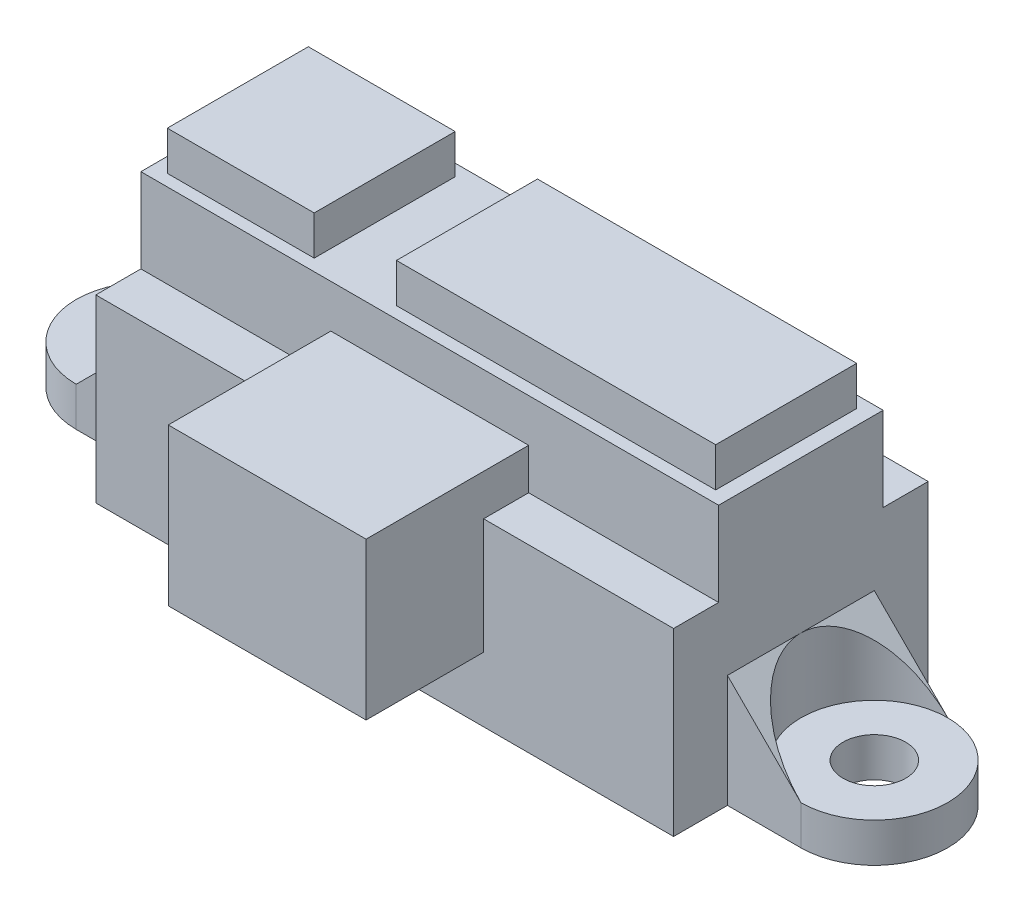
SolidWorks part; units mm, degrees
ref_plane "Plan de face" through (0, 0, 0) normal (0, 0, 1) x (1, 0, 0)
ref_plane "Plan de dessus" through (0, 0, 0) normal (0, 1, 0) x (1, 0, 0)
ref_plane "Plan de droite" through (0, 0, 0) normal (1, 0, 0) x (0, 0, -1)
sketch "Sketch1" plane through (0, 0, 0) normal (0, 1, 0) x (1, 0, 0)
  line L1 (-18.5, -3.75) -> (18.5, -3.75)
  line L2 (-18.5, -3.75) -> (-18.5, 3.75) construction
  line L3 (-18.5, 3.75) -> (18.5, 3.75)
  line L4 (18.5, -3.75) -> (18.5, 3.75) construction
  line L5 (-18.5, -3.75) -> (18.5, 3.75) construction
  line L6 (-18.5, 3.75) -> (18.5, -3.75) construction
  arc A0 (18.5, -3.75) -> (18.5, 3.75) centre (18.5, 0) ccw
  arc A1 (-18.5, 3.75) -> (-18.5, -3.75) centre (-18.5, 0) ccw
  circle A2 centre (18.5, 0) radius 1.6
  circle A3 centre (-18.5, 0) radius 1.6
  point P0 (0, 0)
  dimension "D1" = 3.75
  dimension "D2" = 3.2
  dimension "D3" = 37
extrude "Extrude1" add sketch "Sketch1" along normal blind 10
sketch "Sketch2" plane through (0, 0, 3.75) normal (0, 0, 1) x (1, 0, 0)
  line L0 (-22.25, 0) -> (-18.5, 0) construction
  line L1 (-22.25, 10) -> (-22.25, 0) construction
  line L2 (-22.25, 2) -> (-18.5, 2)
  line L3 (-18.5, 10) -> (-18.5, 0) construction
  line L4 (-18.5, 2) -> (-10.5, 10)
  line L5 (-18.5, 10) -> (18.5, 10) construction
  line L6 (-10.5, 10) -> (10.5, 10)
  line L7 (10.5, 10) -> (18.5, 2)
  line L8 (18.5, 10) -> (18.5, 0) construction
  line L9 (18.5, 2) -> (22.25, 2)
  line L10 (22.25, 2) -> (22.25, 12)
  line L11 (22.25, 12) -> (-22.25, 12)
  line L12 (-22.25, 12) -> (-22.25, 2)
  line L13 (-18.5, 10) -> (-22.25, 10) construction
  line L14 (22.25, 0) -> (22.25, 10) construction
  dimension "D1" = 2
  dimension "D2" = 2
  dimension "D3" = 45
  dimension "D4" = 45
extrude "Extrude2" cut sketch "Sketch2" against normal blind 10
sketch "Sketch3" plane through (0, 2, 0) normal (0, 1, 0) x (1, 0, 0)
  circle A0 centre (-18.5, 0) radius 3.75
  circle A1 centre (18.5, 0) radius 3.75
extrude "Extrude3" cut sketch "Sketch3" along normal blind 10
sketch "Sketch4" plane through (0, 0, 0) normal (0, -1, 0) x (1, 0, 0)
  line L1 (-14.75, -6.5) -> (14.75, -6.5)
  line L2 (-14.75, -6.5) -> (-14.75, 6.5)
  line L3 (-14.75, 6.5) -> (14.75, 6.5)
  line L4 (14.75, -6.5) -> (14.75, 6.5)
  line L5 (-14.75, -6.5) -> (14.75, 6.5) construction
  line L6 (-14.75, 6.5) -> (14.75, -6.5) construction
  point P0 (0, 0)
  dimension "D1" = 13
  dimension "D2" = 29.5
extrude "Extrude4" add sketch "Sketch4" against normal blind 9.2
sketch "Sketch5" plane through (0, 9.2, 0) normal (0, 1, 0) x (1, 0, 0)
  line L0 (14.75, 6.5) -> (14.75, -6.5) construction
  line L1 (-14.75, -4.2) -> (14.75, -4.2)
  line L2 (-14.75, -4.2) -> (-14.75, 4.2)
  line L3 (-14.75, 4.2) -> (14.75, 4.2)
  line L4 (14.75, -4.2) -> (14.75, 4.2)
  line L5 (-14.75, -4.2) -> (14.75, 4.2) construction
  line L6 (-14.75, 4.2) -> (14.75, -4.2) construction
  point P0 (0, 0)
  dimension "D1" = 8.4
extrude "Extrude5" add sketch "Sketch5" along normal blind 4.3
sketch "Sketch6" plane through (0, 13.5, 0) normal (0, 1, 0) x (1, 0, 0)
  line L0 (-10.25, 0) -> (5.85, 0) construction
  line L1 (-14.75, 4.2) -> (-14.75, -4.2) construction
  line L2 (-14, -3.6) -> (-6.5, -3.6)
  line L3 (-14, -3.6) -> (-14, 3.6)
  line L4 (-14, 3.6) -> (-6.5, 3.6)
  line L5 (-6.5, -3.6) -> (-6.5, 3.6)
  line L6 (-14, -3.6) -> (-6.5, 3.6) construction
  line L7 (-14, 3.6) -> (-6.5, -3.6) construction
  line L8 (14, -3.6) -> (-2.3, -3.6)
  line L9 (14, -3.6) -> (14, 3.6)
  line L10 (14, 3.6) -> (-2.3, 3.6)
  line L11 (-2.3, -3.6) -> (-2.3, 3.6)
  line L12 (14, -3.6) -> (-2.3, 3.6) construction
  line L13 (14, 3.6) -> (-2.3, -3.6) construction
  dimension "D1" = 7.5
  dimension "D2" = 4.2
  dimension "D3" = 16.3
  dimension "D4" = 4.5
  dimension "D5" = 7.2
extrude "Extrude6" add sketch "Sketch6" along normal blind 2
sketch "Sketch7" plane through (0, 0, 0) normal (0, 0, 1) x (1, 0, 0)
  line L0 (0, 7.3) -> (0, 0) construction
  line L1 (-5.05, 3.3) -> (5.05, 3.3)
  line L2 (-5.05, 3.3) -> (-5.05, 11.3)
  line L3 (-5.05, 11.3) -> (5.05, 11.3)
  line L4 (5.05, 3.3) -> (5.05, 11.3)
  line L5 (-5.05, 3.3) -> (5.05, 11.3) construction
  line L6 (-5.05, 11.3) -> (5.05, 3.3) construction
  line L7 (14.75, 0) -> (-14.75, 0) construction
  point P0 (0, 7.3)
  dimension "D1" = 10.1
  dimension "D2" = 3.3
  dimension "D3" = 8
extrude "Extrude7" add sketch "Sketch7" along normal blind 12.5
